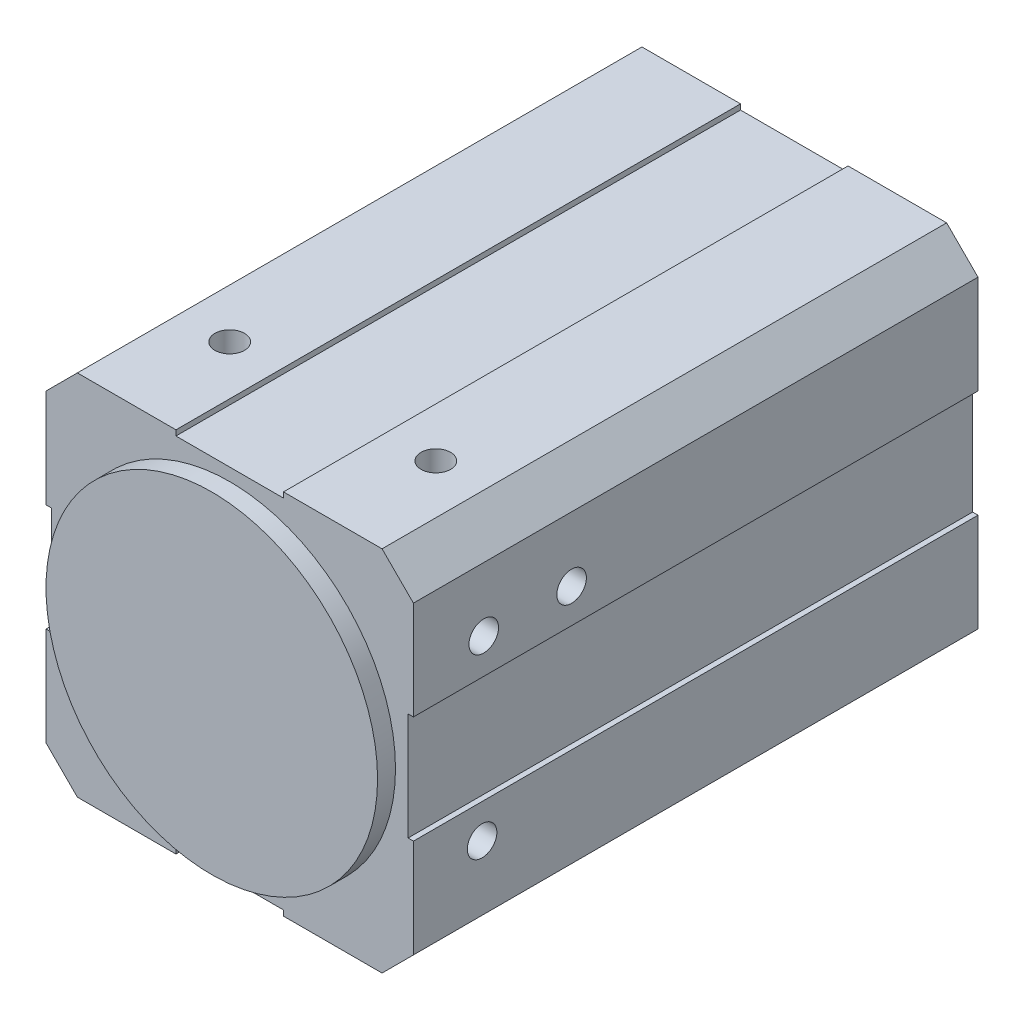
SolidWorks part; units mm, degrees
material "铸造合金钢"
ref_plane "前视基准面" through (0, 0, 0) normal (0, 0, 1) x (1, 0, 0)
ref_plane "上视基准面" through (0, 0, 0) normal (0, 1, 0) x (1, 0, 0)
ref_plane "右视基准面" through (0, 0, 0) normal (1, 0, 0) x (0, 0, -1)
sketch "草图1" plane through (0, 0, 0) normal (0, 1, 0) x (1, 0, 0)
  line L1 (-20.5, 31.5) -> (20.5, 31.5)
  line L2 (-20.5, 31.5) -> (-20.5, -31.5)
  line L3 (-20.5, -31.5) -> (20.5, -31.5)
  line L4 (20.5, 31.5) -> (20.5, -31.5)
  line L5 (-20.5, 31.5) -> (20.5, -31.5) construction
  line L6 (-20.5, -31.5) -> (20.5, 31.5) construction
  point P0 (0, 0)
  dimension "D1" = 41
  dimension "D2" = 63
extrude "凸台-拉伸1" add sketch "草图1" along normal blind 41
sketch "草图2" plane through (0, 41, 0) normal (0, 1, 0) x (1, 0, 0)
  line L0 (-11.5, -20) -> (11.5, -20) construction
  line L1 (0, -31.5) -> (0, 31.5) construction
  line L2 (-20.5, -31.5) -> (20.5, -31.5) construction
  line L3 (20.5, 31.5) -> (-20.5, 31.5) construction
  point P8 (0, -20)
  dimension "D1" = 23
  dimension "D2" = 11.5
hole_wizard "M4 螺纹孔1" positions "3D草图1" profile "草图3" tap size "M4" standard "GB"
sketch3d "3D草图1"
  point P0 (-11.5, 41, 20)
  point P3 (11.5, 41, 20)
sketch "草图3" plane through (-11.5, 41, 20) normal (1, 0, 0) x (0, 0, 1)
  line L0 (0, 0) -> (0, 6.9914)
  line L1 (0, 6.9914) -> (1.65, 6)
  line L2 (1.65, 6) -> (1.65, 0)
  line L5 (1.65, 0) -> (0, 0)
  line L10 (0, 6.9914) -> (-1.65, 6) construction
  line L11 (0, -6.35) -> (0, 107.95) construction
  dimension "螺纹孔钻头直径" = 3.3
  dimension "螺纹孔钻头深度" = 6
  dimension "导头角度" = 118
cosmetic thread "孔螺蚊线1" parameters "D1"=6, "D2"=4
cosmetic thread "孔螺蚊线2" parameters "D1"=6, "D2"=4
ref_plane "基准面1" through (0, 20.5, 0) normal (0, 1, 0) x (1, 0, 0)
mirror "镜向1" about plane through (0, 20.5, 0) normal (0, 1, 0) of "M4 螺纹孔1"
cosmetic thread "孔螺蚊线3" parameters "D1"=6, "D2"=4
cosmetic thread "孔螺蚊线4" parameters "D1"=6, "D2"=4
chamfer "倒角1" distance 3.5 angle 45 4 edges at (-20.5, 0, 0) (20.5, 0, 0) (-20.5, 41, 0) (20.5, 41, 0)
sketch "草图4" plane through (0, 0, 31.5) normal (0, 0, 1) x (1, 0, 0)
  line L0 (0, 41) -> (0, 0) construction
  line L1 (-11.5, 41) -> (11.5, 41) construction
  line L2 (-6, 40.4) -> (6, 40.4)
  line L3 (6, 40.4) -> (6, 41)
  line L4 (-6, 40.4) -> (-6, 41)
  line L5 (-6, 41) -> (6, 41)
  line L6 (19.9, 26.5) -> (19.9, 14.5)
  line L7 (19.9, 14.5) -> (20.5, 14.5)
  line L8 (19.9, 26.5) -> (20.5, 26.5)
  line L9 (20.5, 26.5) -> (20.5, 14.5)
  line L10 (6, 0.6) -> (-6, 0.6)
  line L11 (-6, 0.6) -> (-6, 0)
  line L12 (6, 0.6) -> (6, 0)
  line L13 (6, 0) -> (-6, 0)
  line L14 (-19.9, 14.5) -> (-19.9, 26.5)
  line L15 (-19.9, 26.5) -> (-20.5, 26.5)
  line L16 (-19.9, 14.5) -> (-20.5, 14.5)
  line L17 (-20.5, 14.5) -> (-20.5, 26.5)
  point P8 (0, 40.4)
  point P15 (19.9, 20.5)
  point P20 (0, 0.6)
  point P25 (-19.9, 20.5)
  point P28 (0, 20.5)
  dimension "D1" = 0.6
  dimension "D2" = 12
  dimension "D3" = 4
extrude "切除-拉伸1" cut sketch "草图4" against normal up to next
sketch "草图5" plane through (0, 0, 31.5) normal (0, 0, 1) x (1, 0, 0)
  line L0 (0, 41) -> (0, 0) construction
  line L1 (-11.5, 41) -> (11.5, 41) construction
  circle A0 centre (0, 20.5) radius 18.5
  dimension "D1" = 37
extrude "凸台-拉伸2" add sketch "草图5" along normal blind 2
hole_wizard "M4 螺纹孔3" positions "3D草图7" profile "草图8" tap size "M4" standard "GB"
sketch3d "3D草图7"
  line L0 (19.9, 26.5, -31.5) -> (19.9, 26.5, 31.5) construction
  point P0 (20.5, 30.4054, 23.651)
  point P2 (20.5, 30.3065, 13.851)
  point P4 (20.5, 10.7044, 23.8396)
  point P6 (19.9, 26.5, 9.6193)
  point P10 (-20.5, 7.6875, -0.9824)
sketch "草图8" plane through (20.5, 30.4054, 23.651) normal (0, 1, 0) x (0, 0, -1)
  line L0 (0, 0) -> (0, 11.0914)
  line L1 (0, 11.0914) -> (1.65, 10.1)
  line L2 (1.65, 10.1) -> (1.65, 0)
  line L5 (1.65, 0) -> (0, 0)
  line L10 (0, 11.0914) -> (-1.65, 10.1) construction
  line L11 (0, -6.35) -> (0, 107.95) construction
  dimension "螺纹孔钻头直径" = 3.3
  dimension "螺纹孔钻头深度" = 10.1
  dimension "导头角度" = 118
cosmetic thread "孔螺蚊线8" parameters "D1"=8, "D2"=4
cosmetic thread "孔螺蚊线9" parameters "D1"=8, "D2"=4
cosmetic thread "孔螺蚊线10" parameters "D1"=8, "D2"=4
cosmetic thread "孔螺蚊线11" parameters "D1"=8, "D2"=4
cosmetic thread "孔螺蚊线12" parameters "D1"=8, "D2"=4
